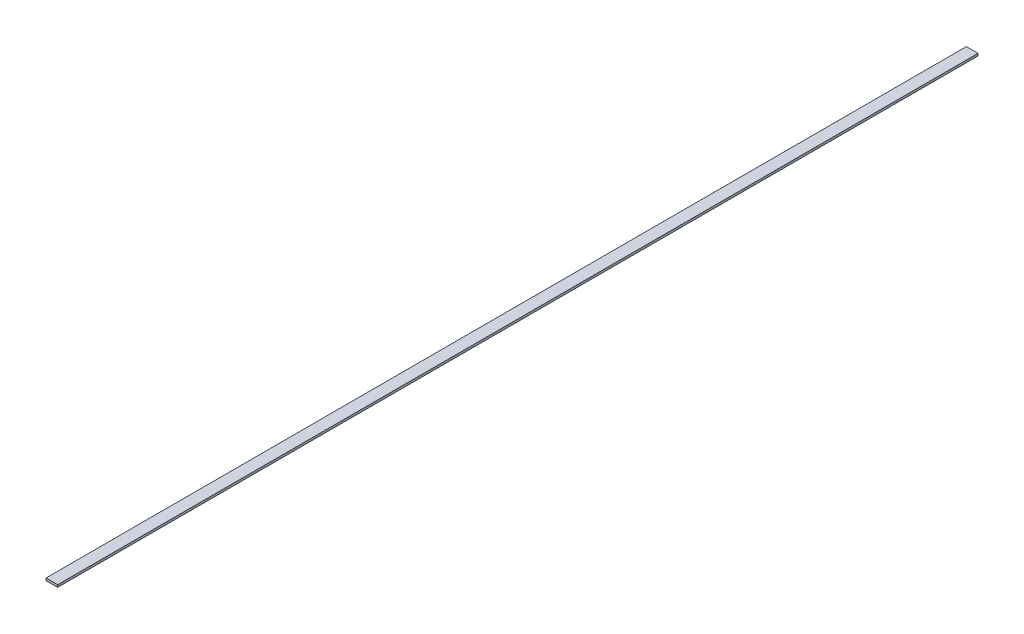
SolidWorks part; units mm, degrees
ref_plane "Front Plane" through (0, 0, 0) normal (0, 0, 1) x (1, 0, 0)
ref_plane "Top Plane" through (0, 0, 0) normal (0, 1, 0) x (1, 0, 0)
ref_plane "Right Plane" through (0, 0, 0) normal (1, 0, 0) x (0, 0, -1)
sketch "Sketch1" plane through (0, 0, 0) normal (0, 0, 1) x (1, 0, 0)
  line L1 (-6.985, 2.4342) -> (18.415, 2.4342)
  line L2 (-6.985, 2.4342) -> (-6.985, -2.6458)
  line L3 (-6.985, -2.6458) -> (18.415, -2.6458)
  line L4 (18.415, 2.4342) -> (18.415, -2.6458)
  dimension "D1" = 5.08
  dimension "D2" = 25.4
extrude "Boss-Extrude1" add sketch "Sketch1" along normal blind 2006.6
